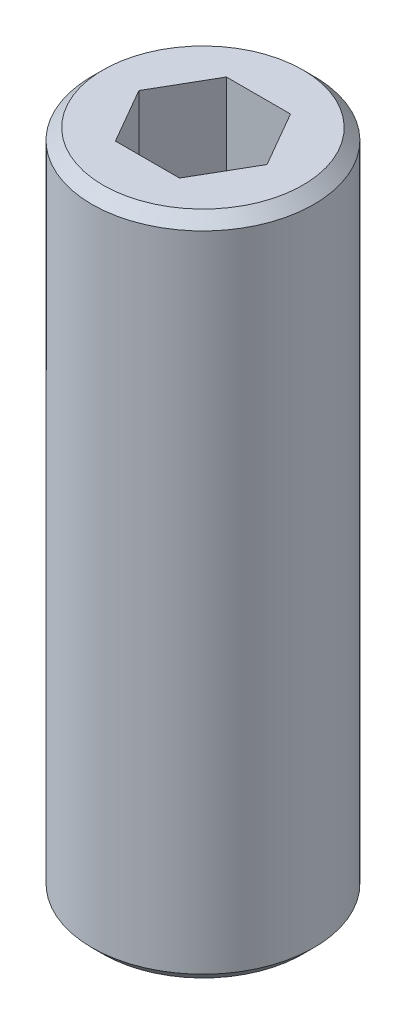
SolidWorks part; units mm, degrees
ref_plane "前视基准面" through (0, 0, 0) normal (0, 0, 1) x (1, 0, 0)
ref_plane "上视基准面" through (0, 0, 0) normal (0, 1, 0) x (1, 0, 0)
ref_plane "右视基准面" through (0, 0, 0) normal (1, 0, 0) x (0, 0, -1)
sketch "草图1" plane through (0, 0, 0) normal (0, 1, 0) x (1, 0, 0)
  circle A0 centre (0, 0) radius 2
  dimension "D1" = 4
extrude "凸台-拉伸1" add sketch "草图1" along normal blind 12
chamfer "倒角1" distance 0.2 angle 45 2 edges at (0, 0, 2) (0, 12, 2)
sketch "草图2" plane through (0, 12, 0) normal (0, 1, 0) x (1, 0, 0)
  line L1 (-1.1547, 0) -> (-0.5774, -1)
  line L2 (-0.5774, -1) -> (0.5774, -1)
  line L3 (0.5774, -1) -> (1.1547, 0)
  line L4 (1.1547, 0) -> (0.5774, 1)
  line L5 (0.5774, 1) -> (-0.5774, 1)
  line L6 (-0.5774, 1) -> (-1.1547, 0)
  circle A0 centre (0, 0) radius 1 construction
  dimension "D1" = 2
extrude "切除-拉伸1" cut sketch "草图2" against normal blind 5
